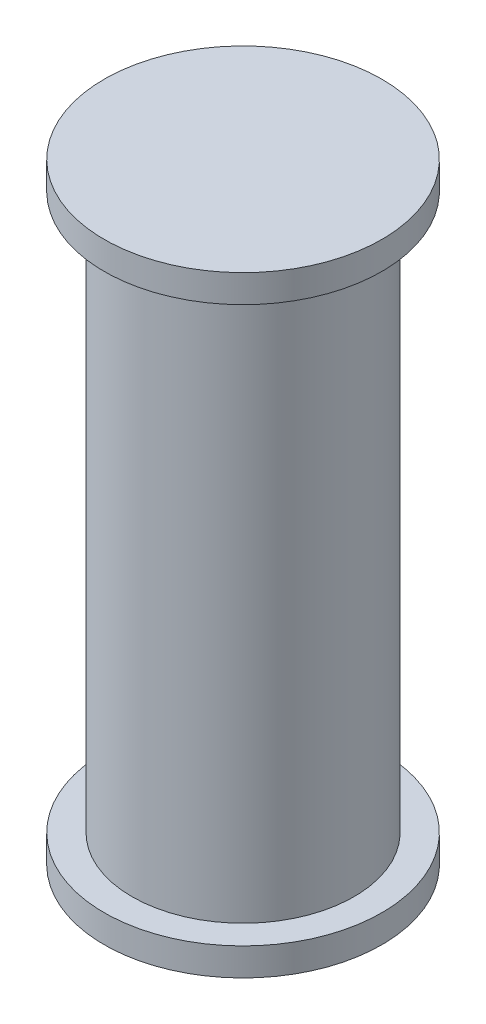
SolidWorks part; units mm, degrees
material "AISI 1045 Steel, cold drawn"
ref_plane "Front Plane" through (0, 0, 0) normal (1, 0, 0) x (0, 1, 0)
ref_plane "Top Plane" through (0, 0, 0) normal (0, 0, 1) x (0, 1, 0)
ref_plane "Right Plane" through (0, 0, 0) normal (0, 1, 0) x (-1, 0, 0)
sketch "Sketch1" plane through (0, 0, 0) normal (1, 0, 0) x (0, 1, 0)
  line L0 (-12.0734, 0) -> (14.9346, 0) construction
  line L1 (0, 9.088) -> (0, -8.64) construction
  line L2 (-10, 4) -> (10, 4)
  line L3 (10, 4) -> (10, 5)
  line L4 (10, 5) -> (11, 5)
  line L5 (11, 5) -> (11, 0)
  line L6 (11, 0) -> (-11, 0)
  line L7 (-11, 0) -> (-11, 5)
  line L8 (-11, 5) -> (-10, 5)
  line L9 (-10, 5) -> (-10, 4)
  point P12 (0, 4)
  dimension "D1" = 8
  dimension "D2" = 10
  dimension "D3" = 1
  dimension "D4" = 22
  dimension "D5" = 1
revolve "Revolve1" add sketch "Sketch1" angle 360 about L0
